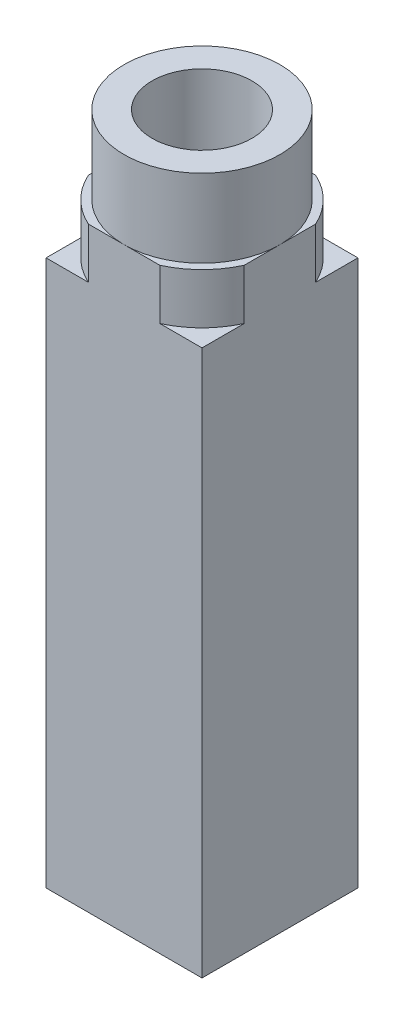
SolidWorks part; units mm, degrees
ref_plane "Front Plane" through (0, 0, 0) normal (0, 0, 1) x (1, 0, 0)
ref_plane "Top Plane" through (0, 0, 0) normal (0, 1, 0) x (1, 0, 0)
ref_plane "Right Plane" through (0, 0, 0) normal (1, 0, 0) x (0, 0, -1)
other "Configuration Table"
sketch "Sketch1" plane through (0, 0, 0) normal (0, 1, 0) x (1, 0, 0)
  line L1 (-3.175, 3.175) -> (3.175, 3.175)
  line L2 (-3.175, 3.175) -> (-3.175, -3.175)
  line L3 (-3.175, -3.175) -> (3.175, -3.175)
  line L4 (3.175, 3.175) -> (3.175, -3.175)
  line L5 (-3.175, 3.175) -> (3.175, -3.175) construction
  line L6 (-3.175, -3.175) -> (3.175, 3.175) construction
  point P0 (0, 0)
  dimension "D1" = 6.35
extrude "Boss-Extrude1" add sketch "Sketch1" along normal blind 22.225
sketch "Sketch2" plane through (0, 0, 0) normal (0, -1, 0) x (1, 0, 0)
  line L0 (3.175, 3.175) -> (3.175, -3.175) construction
  circle A0 centre (0, 0) radius 3.175
extrude "Boss-Extrude2" add sketch "Sketch2" against normal blind 27.4549
ref_plane "Plane1" through (0, 24.2799, 0) normal (0, 1, 0) x (1, 0, 0)
sketch "Sketch4" plane through (0, 24.2799, 0) normal (0, 1, 0) x (1, 0, 0)
  line L0 (-3.175, 0) -> (-3.175, -3.175) construction
  line L1 (0, -3.175) -> (3.175, -3.175) construction
  line L2 (-3.175, -3.175) -> (0, -3.175) construction
  line L3 (3.175, -3.175) -> (3.175, 0) construction
  line L4 (3.175, 0) -> (3.175, 3.175) construction
  line L5 (3.175, 3.175) -> (0, 3.175) construction
  line L6 (0, 3.175) -> (-3.175, 3.175) construction
  line L7 (-3.175, 3.175) -> (-3.175, 0) construction
  line L8 (-3.175, 0) -> (-3.175, -1.455)
  line L9 (0, -3.175) -> (1.455, -3.175)
  line L10 (-1.455, -3.175) -> (0, -3.175)
  line L11 (3.175, -1.455) -> (3.175, 0)
  line L12 (3.175, 0) -> (3.175, 1.455)
  line L13 (1.455, 3.175) -> (0, 3.175)
  line L14 (0, 3.175) -> (-1.455, 3.175)
  line L15 (-3.175, 1.455) -> (-3.175, 0)
  arc A0 (-3.175, -1.455) -> (-1.455, -3.175) centre (0, 0) ccw
  arc A1 (-1.455, 3.175) -> (-3.175, 1.455) centre (0, 0) ccw
  arc A2 (3.175, 1.455) -> (1.455, 3.175) centre (0, 0) ccw
  arc A3 (1.455, -3.175) -> (3.175, -1.455) centre (0, 0) ccw
  dimension "D1" = 6.985
extrude "Boss-Extrude3" add sketch "Sketch4" against normal up to surface (2.0549 mm away) up to face at (-2.3359, 22.225, 2.3359)
sketch "Sketch5" plane through (0, 0, 0) normal (0, -1, 0) x (1, 0, 0)
  circle A0 centre (0, 0) radius 1.9844
  dimension "D1" = 3.9688
extrude "Cut-Extrude1" cut sketch "Sketch5" against normal blind 12.7
sketch "Sketch6" plane through (0, 27.4549, 0) normal (0, 1, 0) x (1, 0, 0)
  circle A0 centre (0, 0) radius 2.032
  dimension "D1" = 4.064
extrude "Cut-Extrude2" cut sketch "Sketch6" against normal blind 12.7
